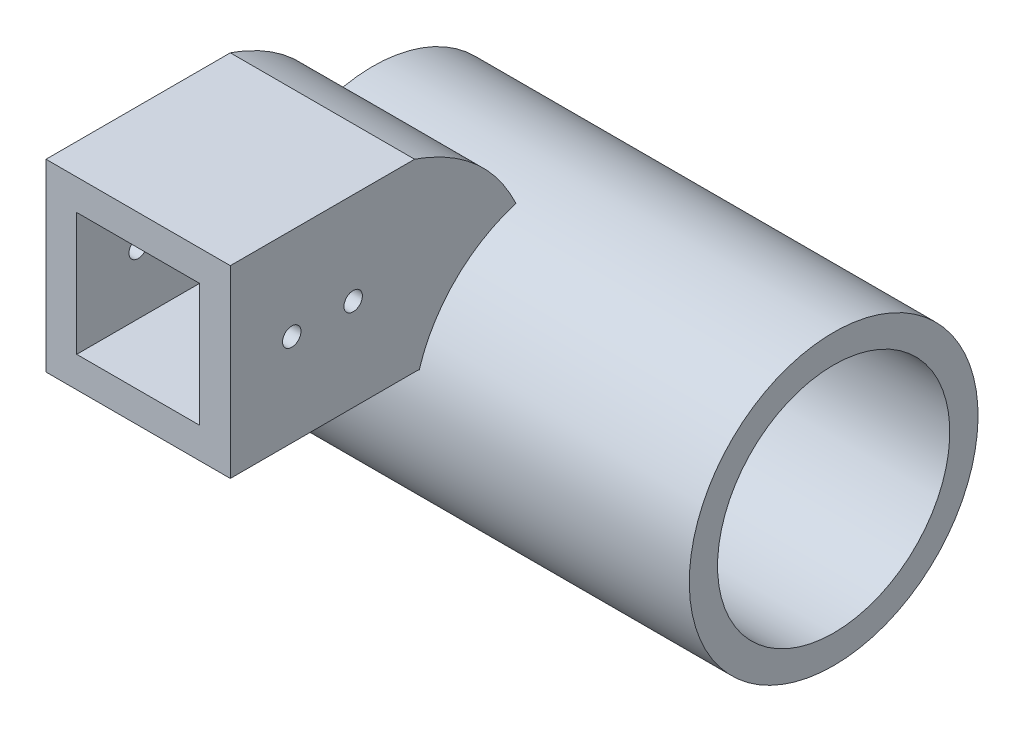
SolidWorks part; units mm, degrees
ref_plane "Front Plane" through (0, 0, 0) normal (0, 0, 1) x (1, 0, 0)
ref_plane "Top Plane" through (0, 0, 0) normal (0, 1, 0) x (1, 0, 0)
ref_plane "Right Plane" through (0, 0, 0) normal (1, 0, 0) x (0, 0, -1)
sketch "Sketch1" plane through (0, 0, 0) normal (0, 0, 1) x (1, 0, 0)
  line L15 (-10, 10) -> (10, 10)
  line L34 (-10, 10) -> (-10, -10)
  line L35 (-10, -10) -> (10, -10)
  line L50 (10, 10) -> (10, -10)
  line L51 (-10, 10) -> (10, -10) construction
  line L66 (-10, -10) -> (10, 10) construction
  line L69 (-15, 15) -> (15, 15)
  line L70 (-15, 15) -> (-15, -15)
  line L71 (-15, -15) -> (15, -15)
  line L72 (15, 15) -> (15, -15)
  point P1 (0, 0)
  dimension "D2" = 20
  dimension "D3" = 20
  dimension "D13" = 30
extrude "Boss-Extrude1" add sketch "Sketch1" along normal blind 30
sketch "Sketch13" plane through (0, 0, 30) normal (0, 0, 1) x (1, 0, 0)
  line L1 (15, 15) -> (-15, 15)
  line L2 (15, 15) -> (15, -15)
  line L3 (15, -15) -> (-15, -15)
  line L4 (-15, 15) -> (-15, -15)
sketch "Sketch21" plane through (15, 0, 0) normal (1, 0, 0) x (0, 0, -1)
  line L0 (0, 15) -> (0, -15) construction
  circle A0 centre (-10, 0) radius 1.5
  circle A1 centre (-20, 0) radius 1.5
  dimension "D1" = 3
  dimension "D3" = 3
  dimension "D2" = 10
  dimension "D4" = 10
extrude "Cut-Extrude1" cut sketch "Sketch21" against normal through all
sketch "Sketch22" plane through (0, 0, 0) normal (0, 0, -1) x (-1, 0, 0)
  line L1 (-15, 15) -> (15, 15)
  line L2 (-15, 15) -> (-15, -15)
  line L3 (-15, -15) -> (15, -15)
  line L4 (15, 15) -> (15, -15)
  line L5 (-15, 15) -> (15, -15) construction
  line L6 (-15, -15) -> (15, 15) construction
  point P0 (0, 0)
extrude "Boss-Extrude2" add sketch "Sketch22" against normal blind 5
sketch "Sketch25" plane through (0, 0, 0) normal (1, 0, 0) x (0, 0, -1)
  line L0 (0, -15) -> (0, -20) construction
  line L1 (0, -20) -> (3.5355, -16.4645) construction
  line L3 (0, 15) -> (0, -15)
  line L5 (3.5355, -16.4645) -> (22.8522, -35.7811)
  line L6 (17.6777, -2.3223) -> (36.9943, -21.639)
  line L7 (22.8522, -35.7811) -> (36.9943, -21.639)
  arc A0 (0, -15) -> (3.5355, -16.4645) centre (0, -20) cw
  spline S0 degree 2 poles (0, 15) (13.0712, 10.4534) (17.6777, -2.3223) knots 0 0 0 1 1 1
  dimension "D1" = 5
  dimension "D2" = 45
  dimension "D3" = 25
  dimension "D5" = 41.46
extrude "Boss-Extrude4" add sketch "Sketch25" along normal mid plane 30
sketch "Sketch26" plane through (-15, 0, 0) normal (-1, 0, 0) x (0, 0, 1)
  line L0 (-29.9232, -28.71) -> (-23.2057, -21.9925) construction
  line L1 (-22.8522, -35.7811) -> (-36.9943, -21.639) construction
  circle A0 centre (-23.2057, -21.9925) radius 23.5
  dimension "D2" = 47
  dimension "D1" = 9.5
extrude "Boss-Extrude5" add sketch "Sketch26" against normal blind 75
sketch "Sketch27" plane through (-15, 0, 0) normal (-1, 0, 0) x (0, 0, 1)
  circle A0 centre (-23.2057, -21.9925) radius 18.9
  arc A1 (-16.4959, 0.5292) -> (-0.7525, -15.057) centre (-23.2057, -21.9925) ccw construction
  dimension "D1" = 37.8
extrude "Cut-Extrude2" cut sketch "Sketch27" against normal through all
sketch "Sketch28" plane through (-15, 0, 0) normal (-1, 0, 0) x (0, 0, 1)
  circle A0 centre (-23.2057, -21.9925) radius 18.9
  circle A1 centre (-23.2057, -21.9925) radius 18.9 construction
extrude "Boss-Extrude7" add sketch "Sketch28" against normal blind 5
sketch "Sketch29" plane through (-15, 0, 0) normal (-1, 0, 0) x (0, 0, 1)
  line L0 (-23.2057, 1.5075) -> (-23.2057, -45.4925) construction
  line L1 (-23.2057, -21.9925) -> (-37.5994, -7.5989) construction
  line L2 (-23.2057, -21.9925) -> (-29.9232, -28.71) construction
  arc A0 (-16.4959, 0.5292) -> (-0.7525, -15.057) centre (-23.2057, -21.9925) ccw construction
  circle A1 centre (-34.4487, -10.7495) radius 1.5
  circle A2 centre (-19.0905, -6.6343) radius 1.5
  circle A3 centre (-7.8475, -17.8773) radius 1.5
  circle A4 centre (-11.9627, -33.2355) radius 1.5
  circle A5 centre (-27.321, -37.3508) radius 1.5
  circle A6 centre (-38.564, -26.1078) radius 1.5
  circle A7 centre (-29.9232, -28.71) radius 2.5
  dimension "D2" = 3
  dimension "D6" = 5
  dimension "D1" = 45
  dimension "D3" = 15.9
  dimension "D5" = 9.5
  dimension "D4" = 6
extrude "Cut-Extrude3" cut sketch "Sketch29" against normal blind 8
